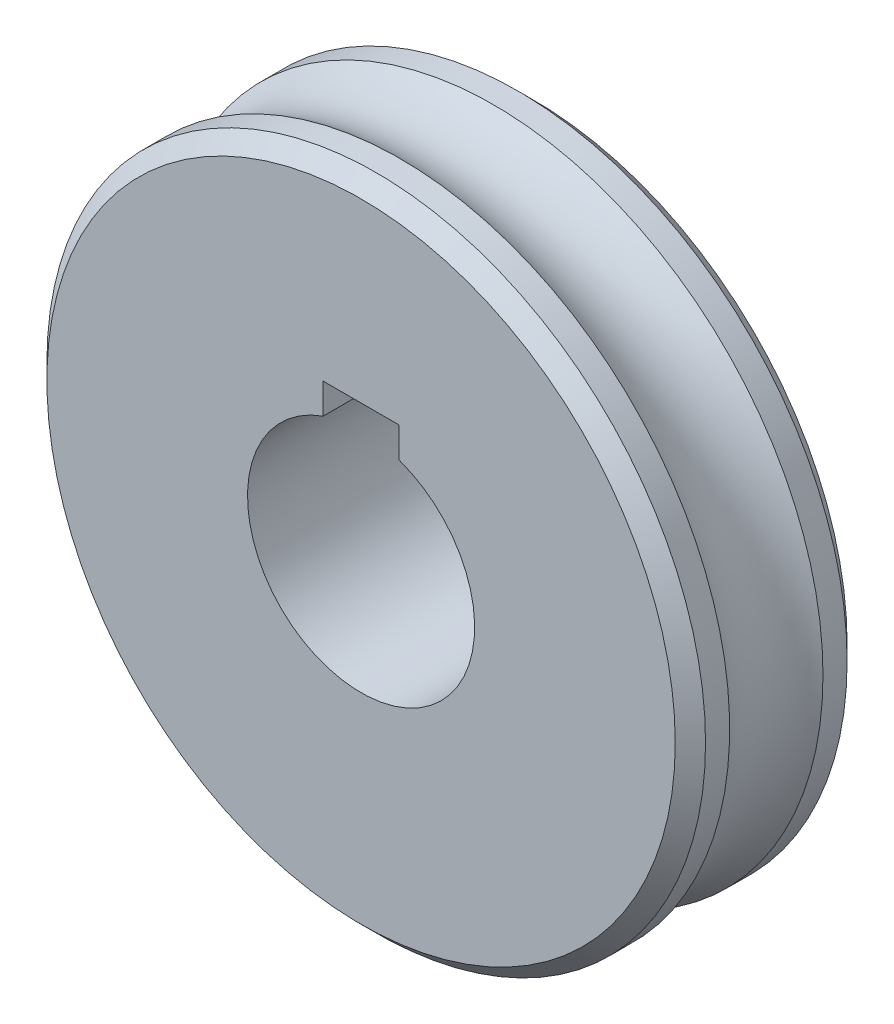
SolidWorks part; units mm, degrees
ref_plane "Front Plane" through (0, 0, 0) normal (0, 0, 1) x (1, 0, 0)
ref_plane "Top Plane" through (0, 0, 0) normal (0, 1, 0) x (1, 0, 0)
ref_plane "Right Plane" through (0, 0, 0) normal (1, 0, 0) x (0, 0, -1)
sketch "Sketch1" plane through (0, 0, 0) normal (0, 0, 1) x (1, 0, 0)
  line L0 (0, -5) -> (0, 5) construction
  line L2 (-5, 18.1421) -> (5, 18.1421)
  line L3 (-5, 18.1421) -> (-5, 14.1421)
  line L5 (5, 18.1421) -> (5, 14.1421)
  arc A0 (-5, 14.1421) -> (5, 14.1421) centre (0, 0) ccw
  circle A1 centre (0, 0) radius 43.5
  point P7 (0, 0)
  dimension "D1" = 87
  dimension "D2" = 30
  dimension "D3" = 10
  dimension "D4" = 4
extrude "Boss-Extrude1" add sketch "Sketch1" along normal mid plane 22.7
chamfer "Chamfer1" distance 2 angle 45 2 edges at (43.5, 0, -11.35) (43.5, 0, 11.35)
sketch "Sketch2" plane through (0, 0, 0) normal (1, 0, 0) x (0, 0, -1)
  line L0 (0, -75.5599) -> (0, 75.5599) construction
  line L1 (83.5333, 0) -> (-83.5333, 0) construction
  circle A0 centre (0, -52) radius 10.5
  point P4 (0, 0)
  point P8 (0, 0)
  dimension "D1" = 21
  dimension "D2" = 52
revolve "Cut-Revolve1" cut sketch "Sketch2" angle 360 about L1
sketch "Sketch3" plane through (0, 0, 0) normal (1, 0, 0) x (0, 0, -1)
  circle A1 centre (0, -52) radius 10.5
  circle A2 centre (0, -52) radius 10.5
  point P0 (0, 0)
  dimension "D2" = 52
  dimension "D1" = 0
curve "Helix/Spiral1" pitch 6 height 1.5 turns 0.25
sketch "Sketch4" plane through (0, 0, 0) normal (0, 0, 1) x (1, 0, 0)
  line L0 (0, -70.177) -> (0, 70.177) construction
  line L1 (-3.45, -46.04) -> (3.45, -46.04)
  line L2 (3.45, -46.04) -> (-3.45, -46.04)
  line L3 (-3.45, -42.44) -> (-3.45, -46.04)
  line L4 (3.45, -46.04) -> (3.45, -42.44)
  arc A0 (-1.2018, -37.79) -> (1.2018, -37.79) centre (0, -39.13) cw
  arc A1 (-1.2018, -37.79) -> (-3.45, -42.44) centre (-18.3636, -32.3611) cw
  arc A2 (1.2018, -37.79) -> (3.45, -42.44) centre (18.3636, -32.3611) ccw
  point P5 (0, 0)
  dimension "D2" = 1.8
  dimension "D4" = 18
  dimension "D1" = 39.13
  dimension "D3" = 6.9
  dimension "D5" = 4.65
  dimension "D6" = 1.34
  dimension "D7" = 3.6
